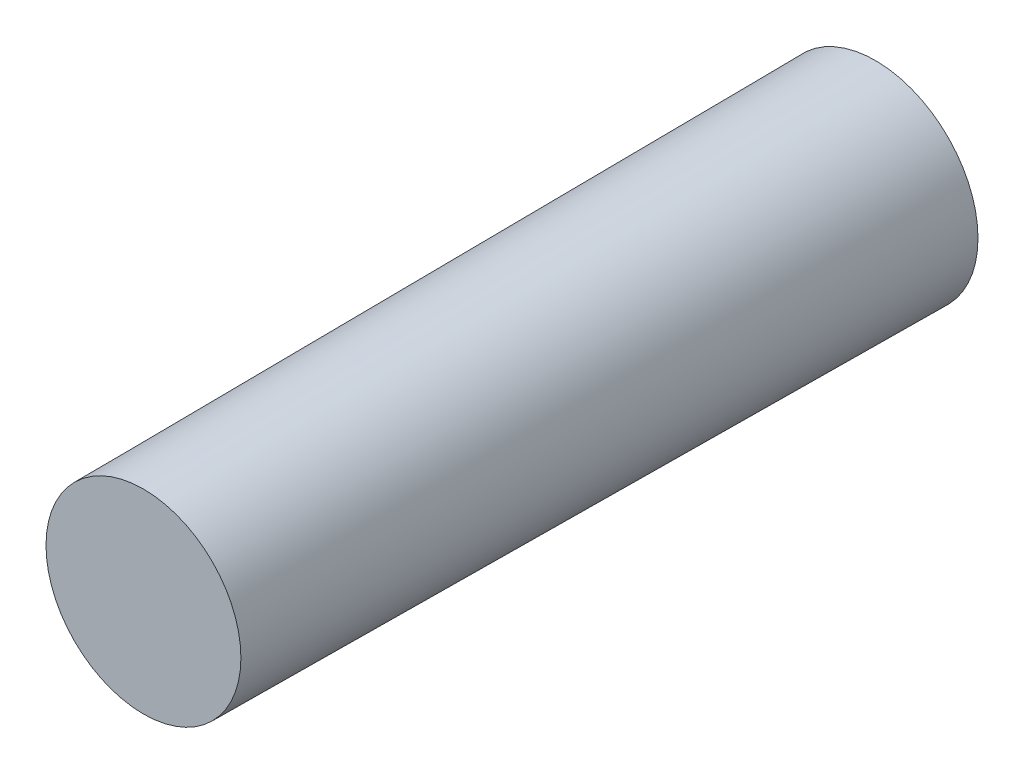
SolidWorks part; units mm, degrees
ref_plane "Front Plane" through (0, 0, 0) normal (0, 0, 1) x (1, 0, 0)
ref_plane "Top Plane" through (0, 0, 0) normal (0, 1, 0) x (1, 0, 0)
ref_plane "Right Plane" through (0, 0, 0) normal (1, 0, 0) x (0, 0, -1)
sketch "Sketch1" plane through (0, 0, 0) normal (0, 0, 1) x (1, 0, 0)
  circle A0 centre (0, 0) radius 7.6835
  dimension "D1" = 15.367
extrude "Boss-Extrude1" add sketch "Sketch1" along normal blind 54.8386 draft 0.4
